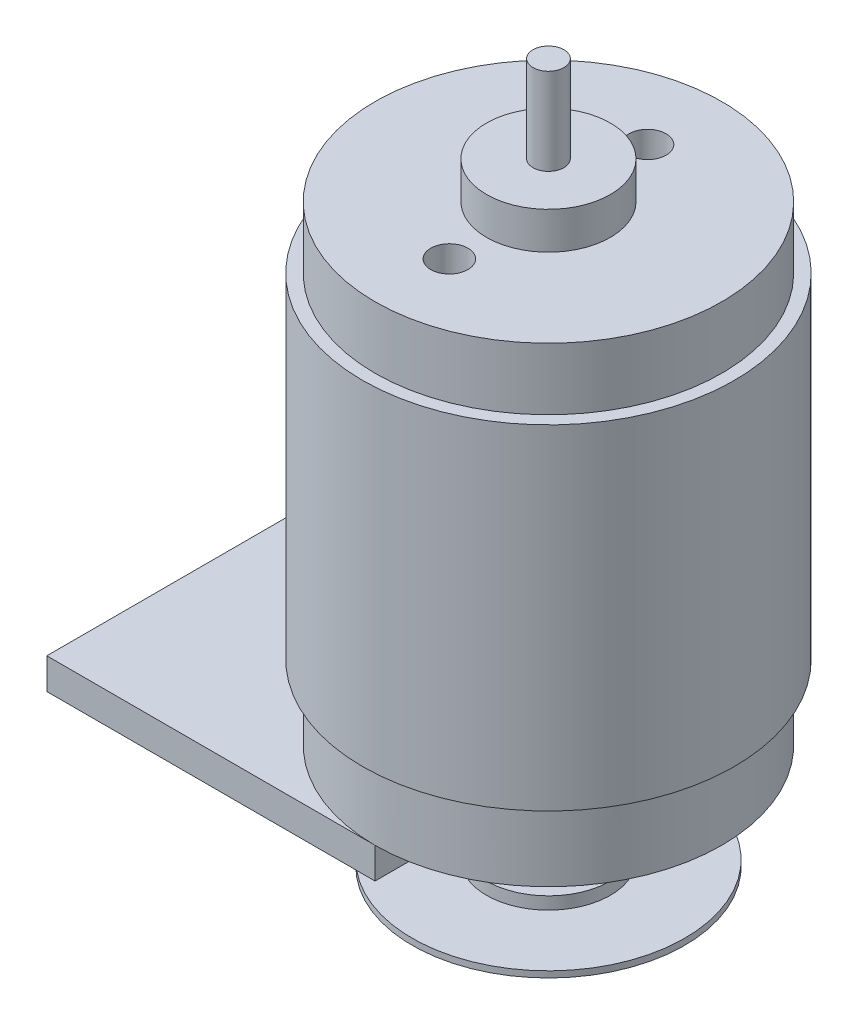
SolidWorks part; units mm, degrees
material "AISI 304"
ref_plane "Front Plane" through (0, 0, 0) normal (0, 0, 1) x (1, 0, 0)
ref_plane "Top Plane" through (0, 0, 0) normal (0, 1, 0) x (1, 0, 0)
ref_plane "Right Plane" through (0, 0, 0) normal (1, 0, 0) x (0, 0, -1)
sketch "Sketch1" plane through (0, 0, 0) normal (0, 1, 0) x (1, 0, 0)
  circle A0 centre (0, 0) radius 15
  dimension "D1" = 30
extrude "Boss-Extrude1" add sketch "Sketch1" along normal blind 27
sketch "Sketch2" plane through (0, 27, 0) normal (0, 1, 0) x (1, 0, 0)
  circle A0 centre (0, 0) radius 14
  dimension "D1" = 28
extrude "Boss-Extrude2" add sketch "Sketch2" along normal blind 5
sketch "Sketch3" plane through (0, 32, 0) normal (0, 1, 0) x (1, 0, 0)
  circle A0 centre (0, 0) radius 5
  dimension "D1" = 10
extrude "Boss-Extrude3" add sketch "Sketch3" along normal blind 3
sketch "Sketch4" plane through (0, 35, 0) normal (0, 1, 0) x (1, 0, 0)
  circle A0 centre (0, 0) radius 1.25
  dimension "D1" = 2.5
extrude "Boss-Extrude4" add sketch "Sketch4" along normal blind 7
sketch "Sketch5" plane through (0, 0, 0) normal (0, -1, 0) x (1, 0, 0)
  circle A0 centre (0, 0) radius 14
  dimension "D1" = 28
extrude "Boss-Extrude5" add sketch "Sketch5" along normal blind 6
sketch "Sketch6" plane through (0, -6, 0) normal (0, -1, 0) x (1, 0, 0)
  circle A0 centre (0, 0) radius 5
  dimension "D1" = 10
extrude "Boss-Extrude6" add sketch "Sketch6" along normal blind 3
sketch "Sketch7" plane through (0, -6, 0) normal (0, -1, 0) x (1, 0, 0)
  line L1 (0, 14) -> (-26.5, 14)
  line L2 (0, 14) -> (0, -14)
  line L3 (0, -14) -> (-26.5, -14)
  line L4 (-26.5, 14) -> (-26.5, -14)
  circle A0 centre (0, 0) radius 14 construction
  circle A1 centre (0, 0) radius 14 construction
  dimension "D1" = 28
  dimension "D2" = 26.5
extrude "Boss-Extrude7" add sketch "Sketch7" along normal blind 2.5
sketch "Sketch8" plane through (0, -9, 0) normal (0, -1, 0) x (1, 0, 0)
  circle A0 centre (0, 0) radius 1.25
  dimension "D1" = 2.5
extrude "Boss-Extrude8" add sketch "Sketch8" along normal blind 4
sketch "Sketch9" plane through (0, -13, 0) normal (0, -1, 0) x (1, 0, 0)
  circle A0 centre (0, 0) radius 5
  dimension "D1" = 10
extrude "Boss-Extrude9" add sketch "Sketch9" along normal blind 1
sketch "Sketch10" plane through (0, -14, 0) normal (0, -1, 0) x (1, 0, 0)
  circle A0 centre (0, 0) radius 11
  dimension "D1" = 22
extrude "Boss-Extrude10" add sketch "Sketch10" along normal blind 0.5
sketch "Sketch11" plane through (0, -14.5, 0) normal (0, -1, 0) x (1, 0, 0)
  circle A0 centre (0, 0) radius 5
  dimension "D1" = 10
extrude "Boss-Extrude11" add sketch "Sketch11" along normal blind 1
sketch "Sketch12" plane through (0, -15.5, 0) normal (0, -1, 0) x (1, 0, 0)
  circle A0 centre (0, 0) radius 1.25
  dimension "D1" = 2.5
extrude "Boss-Extrude12" add sketch "Sketch12" along normal blind 3
sketch "Sketch13" plane through (0, 32, 0) normal (0, 1, 0) x (1, 0, 0)
  circle A0 centre (0, 0) radius 8 construction
  circle A5 centre (0, 8) radius 1.5
  circle A6 centre (0, -8) radius 1.5
  dimension "D1" = 16
  dimension "D2" = 3
  dimension "D3" = 3
extrude "Cut-Extrude1" cut sketch "Sketch13" against normal blind 20
